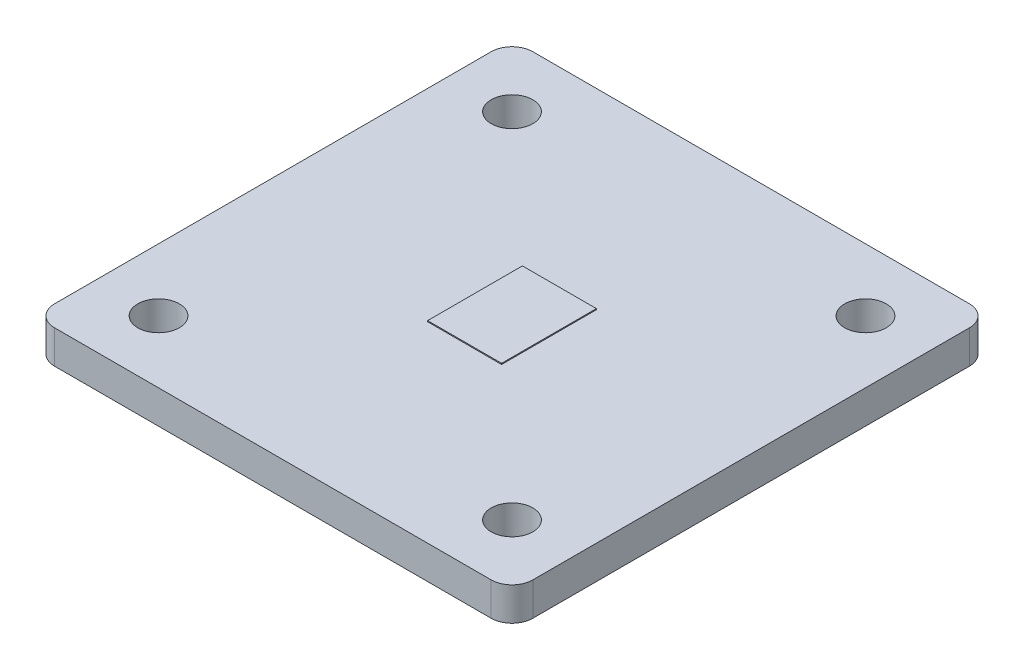
SolidWorks part; units mm, degrees
ref_plane "Front Plane" through (0, 0, 0) normal (0, 0, 1) x (1, 0, 0)
ref_plane "Top Plane" through (0, 0, 0) normal (0, 1, 0) x (1, 0, 0)
ref_plane "Right Plane" through (0, 0, 0) normal (1, 0, 0) x (0, 0, -1)
sketch "Sketch1" plane through (0, 0, 0) normal (0, 1, 0) x (1, 0, 0)
  line L1 (-10.5, -11.5) -> (10.5, -11.5)
  line L2 (-11.5, -10.5) -> (-11.5, 10.5)
  line L3 (-10.5, 11.5) -> (10.5, 11.5)
  line L4 (11.5, -10.5) -> (11.5, 10.5)
  line L5 (-11.5, -11.5) -> (11.5, 11.5) construction
  line L6 (-11.5, 11.5) -> (11.5, -11.5) construction
  arc A0 (10.5, -11.5) -> (11.5, -10.5) centre (10.5, -10.5) ccw
  arc A1 (-10.5, -11.5) -> (-11.5, -10.5) centre (-10.5, -10.5) cw
  arc A2 (-11.5, 10.5) -> (-10.5, 11.5) centre (-10.5, 10.5) cw
  arc A3 (10.5, 11.5) -> (11.5, 10.5) centre (10.5, 10.5) cw
  point P0 (0, 0)
  dimension "D2" = 1
  dimension "D1" = 23
extrude "Boss-Extrude1" add sketch "Sketch1" along normal blind 1.6
sketch "Sketch2" plane through (0, 1.6, 0) normal (0, 1, 0) x (1, 0, 0)
  line L0 (0, 11.5) -> (0, -11.5) construction
  line L1 (10.5, 11.5) -> (-10.5, 11.5) construction
  line L2 (-10.5, -11.5) -> (10.5, -11.5) construction
  line L3 (-11.5, 0) -> (11.5, 0) construction
  line L4 (-11.5, 10.5) -> (-11.5, -10.5) construction
  line L5 (11.5, -10.5) -> (11.5, 10.5) construction
  circle A0 centre (-8.5, 8.5) radius 1
  circle A1 centre (-8.5, -8.5) radius 1
  circle A2 centre (8.5, 8.5) radius 1
  circle A3 centre (8.5, -8.5) radius 1
  dimension "D1" = 2
  dimension "D2" = 17
  dimension "D3" = 17
extrude "Cut-Extrude1" cut sketch "Sketch2" against normal blind 1.6
sketch "Sketch4" plane through (0, 1.6, 0) normal (0, 1, 0) x (1, 0, 0)
  line L1 (-1.7785, -2.2785) -> (1.7785, -2.2785)
  line L2 (-1.7785, -2.2785) -> (-1.7785, 2.2785)
  line L3 (-1.7785, 2.2785) -> (1.7785, 2.2785)
  line L4 (1.7785, -2.2785) -> (1.7785, 2.2785)
  line L5 (-1.7785, -2.2785) -> (1.7785, 2.2785) construction
  line L6 (-1.7785, 2.2785) -> (1.7785, -2.2785) construction
  point P0 (0, 0)
  dimension "D1" = 3.557
  dimension "D2" = 4.557
extrude "Boss-Extrude2" add sketch "Sketch4" along normal blind 0.05
